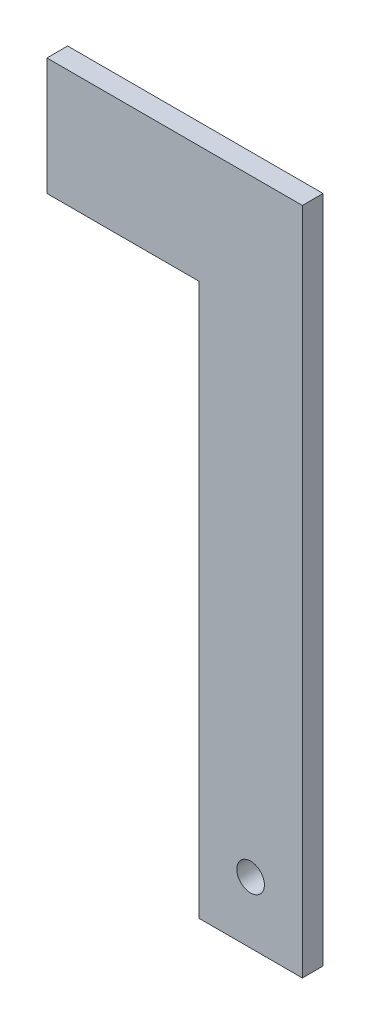
SolidWorks part; units mm, degrees
ref_plane "Alzado" through (0, 0, 0) normal (0, 0, 1) x (1, 0, 0)
ref_plane "Planta" through (0, 0, 0) normal (0, 1, 0) x (1, 0, 0)
ref_plane "Vista lateral" through (0, 0, 0) normal (1, 0, 0) x (0, 0, -1)
sketch "Croquis1" plane through (0, 0, 0) normal (0, 0, 1) x (1, 0, 0)
  line L1 (20, -36.915) -> (20, 60)
  line L2 (20, 60) -> (3, 60)
  line L3 (5, 43) -> (5, -36.915)
  line L8 (3, 60) -> (-17, 60)
  line L9 (-17, 60) -> (-17, 43)
  line L10 (-17, 43) -> (5, 43)
  line L11 (5, -28) -> (20, -28) construction
  line L12 (5, -36.915) -> (20, -36.915)
  circle A1 centre (12.5, -28) radius 2
  dimension "D2" = 4
  dimension "D1" = 22
  dimension "D3" = 8.915
  dimension "D4" = 96.915
  dimension "D5" = 37
  dimension "D6" = 17
extrude "Saliente-Extruir1" add sketch "Croquis1" along normal blind 3
